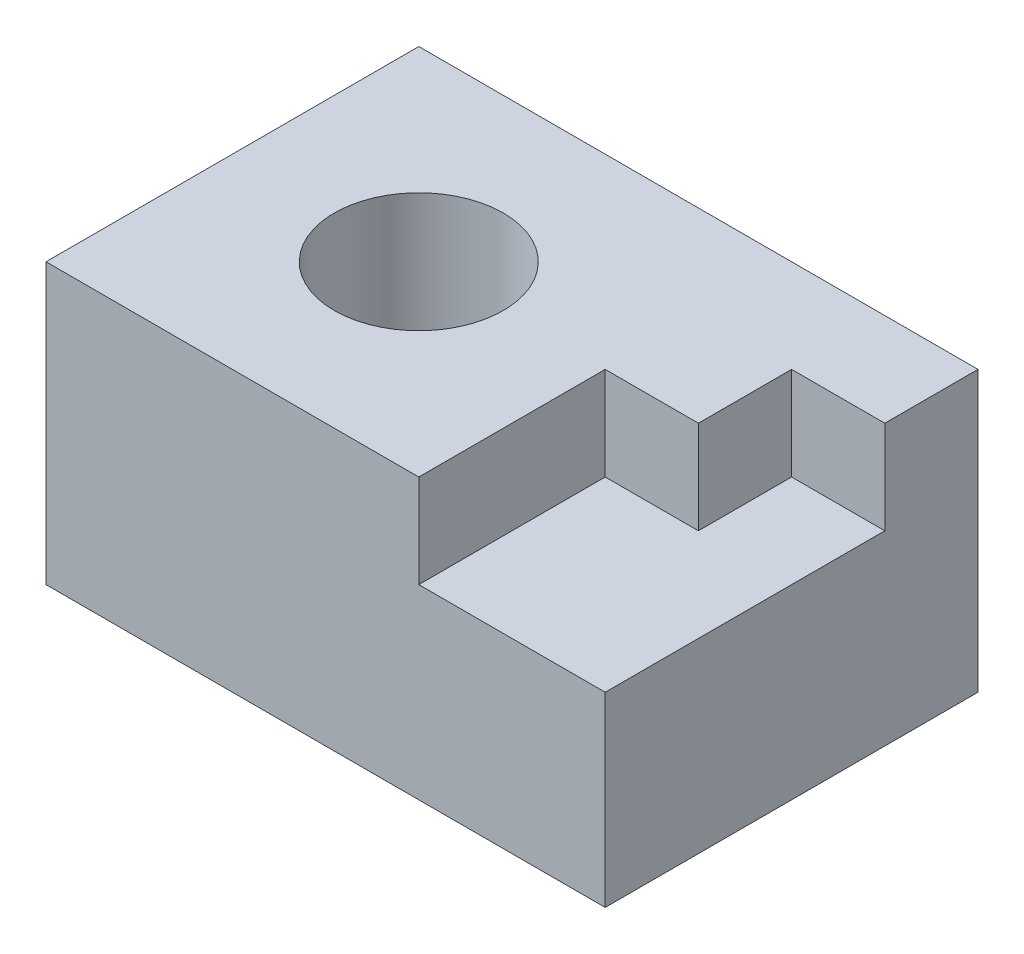
SolidWorks part; units mm, degrees
ref_plane "Front Plane" through (0, 0, 0) normal (0, 0, 1) x (1, 0, 0)
ref_plane "Top Plane" through (0, 0, 0) normal (0, 1, 0) x (1, 0, 0)
ref_plane "Right Plane" through (0, 0, 0) normal (1, 0, 0) x (0, 0, -1)
sketch "Sketch1" plane through (0, 0, 0) normal (0, 1, 0) x (1, 0, 0)
  line L1 (-76.2, -50.8) -> (76.2, -50.8)
  line L2 (-76.2, -50.8) -> (-76.2, 50.8)
  line L3 (-76.2, 50.8) -> (76.2, 50.8)
  line L4 (76.2, -50.8) -> (76.2, 50.8)
  line L5 (-76.2, -50.8) -> (76.2, 50.8) construction
  line L6 (-76.2, 50.8) -> (76.2, -50.8) construction
  point P0 (0, 0)
  dimension "D1" = 152.4
  dimension "D2" = 101.6
extrude "Boss-Extrude1" add sketch "Sketch1" along normal blind 76.2
sketch "Sketch2" plane through (0, 76.2, 0) normal (0, 1, 0) x (1, 0, 0)
  line L1 (76.2, -50.8) -> (25.4, -50.8)
  line L2 (76.2, -50.8) -> (76.2, 15.2101)
  line L3 (50.8, 0) -> (25.4, 0)
  line L4 (25.4, -50.8) -> (25.4, 0)
  line L6 (76.2, 15.2101) -> (76.2, 25.4)
  line L7 (76.2, 25.4) -> (50.8, 25.4)
  line L8 (50.8, 0) -> (50.8, 25.4)
  dimension "D1" = 50.8
  dimension "D2" = 25.4
  dimension "D3" = 25.4
  dimension "D4" = 25.4
extrude "Cut-Extrude1" cut sketch "Sketch2" against normal blind 25.4
sketch "Sketch3" plane through (0, 76.2, 0) normal (0, 1, 0) x (1, 0, 0)
  line L0 (76.2, 50.8) -> (-76.2, 50.8) construction
  line L1 (-76.2, 50.8) -> (-76.2, -50.8) construction
  circle A0 centre (-25.4, 0) radius 23.0337
  dimension "D1" = 50.8
  dimension "D2" = 50.8
extrude "Cut-Extrude2" cut sketch "Sketch3" against normal through all
